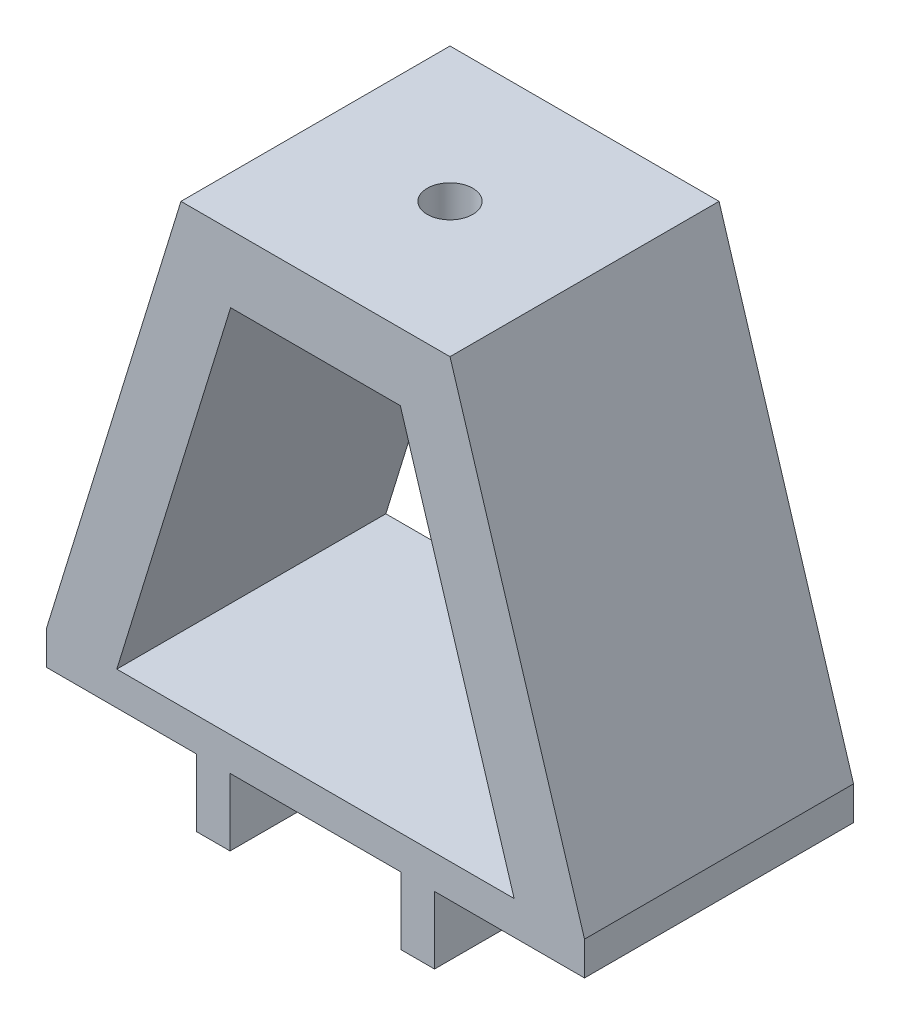
SolidWorks part; units mm, degrees
ref_plane "Front Plane" through (0, 0, 0) normal (0, 0, 1) x (1, 0, 0)
ref_plane "Top Plane" through (0, 0, 0) normal (0, 1, 0) x (1, 0, 0)
ref_plane "Right Plane" through (0, 0, 0) normal (1, 0, 0) x (0, 0, -1)
sketch "Sketch1" plane through (0, 0, 0) normal (0, 1, 0) x (1, 0, 0)
  line L1 (-40, -20) -> (40, -20)
  line L2 (-40, -20) -> (-40, 20)
  line L3 (-40, 20) -> (40, 20)
  line L4 (40, -20) -> (40, 20)
  line L5 (-40, -20) -> (40, 20) construction
  line L6 (-40, 20) -> (40, -20) construction
  point P0 (0, 0)
  dimension "D1" = 40
  dimension "D2" = 80
extrude "Boss-Extrude1" add sketch "Sketch1" along normal blind 5
sketch "Sketch2" plane through (0, 0, 0) normal (0, -1, 0) x (1, 0, 0)
  line L0 (0, -1000) -> (0, 49000) construction
  line L1 (-40, 20) -> (40, 20) construction
  line L2 (12.7, 20) -> (17.7, 20)
  line L3 (12.7, 20) -> (12.7, -20)
  line L4 (12.7, -20) -> (17.7, -20)
  line L5 (17.7, 20) -> (17.7, -20)
  line L6 (40, -20) -> (-40, -20) construction
  line L7 (-12.7, -20) -> (-17.7, -20)
  line L8 (-17.7, 20) -> (-17.7, -20)
  line L9 (-12.7, 20) -> (-17.7, 20)
  line L10 (-12.7, 20) -> (-12.7, -20)
  dimension "D1" = 25.4
  dimension "D2" = 5
extrude "Boss-Extrude2" add sketch "Sketch2" along normal blind 10
sketch "Sketch3" plane through (-17.7, 0, 0) normal (-1, 0, 0) x (0, 0, 1)
  line L0 (-10, -5) -> (10, -5) construction
  line L1 (-20, 0) -> (20, 0) construction
  circle A0 centre (-10, -5) radius 2.2
  circle A1 centre (10, -5) radius 2.2
  point P4 (0, -5)
  dimension "D1" = 4.4
  dimension "D2" = 20
  dimension "D3" = 5
extrude "Cut-Extrude1" cut sketch "Sketch3" against normal through all
sketch "Sketch4" plane through (-17.7, 0, 0) normal (-1, 0, 0) x (0, 0, 1)
  line L1 (-7.8927, -1.35) -> (-12.1073, -1.35)
  line L2 (-12.1073, -1.35) -> (-14.2147, -5)
  line L3 (-14.2147, -5) -> (-12.1073, -8.65)
  line L4 (-12.1073, -8.65) -> (-7.8927, -8.65)
  line L5 (-7.8927, -8.65) -> (-5.7853, -5)
  line L6 (-5.7853, -5) -> (-7.8927, -1.35)
  line L7 (12.1073, -1.35) -> (7.8927, -1.35)
  line L8 (7.8927, -1.35) -> (5.7853, -5)
  line L9 (5.7853, -5) -> (7.8927, -8.65)
  line L10 (7.8927, -8.65) -> (12.1073, -8.65)
  line L11 (12.1073, -8.65) -> (14.2147, -5)
  line L12 (14.2147, -5) -> (12.1073, -1.35)
  circle A0 centre (-10, -5) radius 3.65 construction
  circle A1 centre (10, -5) radius 3.65 construction
  dimension "D1" = 7.3
extrude "Cut-Extrude2" cut sketch "Sketch4" against normal blind 3
sketch "Sketch7" plane through (0, 0, -20) normal (0, 0, -1) x (-1, 0, 0)
  line L0 (0, -1000) -> (0, 49000) construction
  line L1 (-12.6143, 60) -> (12.6143, 60)
  line L2 (12.6143, 60) -> (29.5373, 5)
  line L3 (-40, 5) -> (40, 5) construction
  line L4 (29.5373, 5) -> (40, 5)
  line L5 (40, 5) -> (20, 70)
  line L6 (20, 70) -> (-20, 70)
  line L7 (-12.7, 0) -> (12.7, 0) construction
  line L8 (-40, 5) -> (-20, 70)
  line L9 (-12.6143, 60) -> (-29.5373, 5)
  point P15 (0, 70)
  point P18 (0, 60)
  line M15 (40, 5) -> (-40, 5)
  dimension "D1" = 20
  dimension "D2" = 10
  dimension "D3" = 10
  dimension "D4" = 70
extrude "Boss-Extrude3" add sketch "Sketch7" against normal up to surface (40 mm away) contours L0 L1 L2 L5 L6 M15 | L1 L0 L6 L8 L9 M15 up to face at (0, -2.5, 20)
sketch "Sketch5" plane through (0, 60, 0) normal (0, -1, 0) x (-1, 0, 0)
  point P0 (0, 0)
hole_wizard "CBORE for 1/4 Square Head Bolt1" positions "Sketch5" profile "Sketch6" counterbore size "1/4" standard "ANSI Inch" end condition through all
sketch "Sketch6" plane through (0, 60, 0) normal (1, 0, 0) x (0, 0, -1)
  line L0 (0, 0) -> (0, 10)
  line L1 (0, 10) -> (3.3782, 10)
  line L3 (3.3782, 10) -> (3.3782, 4.7752)
  line L4 (8.3337, 4.7752) -> (3.3782, 4.7752)
  line L5 (8.3337, 4.7752) -> (8.3337, 0.635)
  line L6 (8.3337, 0.635) -> (8.9687, 0)
  line L7 (8.9687, 0) -> (0, 0)
  line L8 (-8.3337, 0.635) -> (-8.9687, 0) construction
  line L11 (0, -6.35) -> (0, 107.95) construction
  dimension "Thru Hole Dia." = 6.7564
  dimension "Thru Hole Depth" = 10
  dimension "C'Bore Dia." = 16.6675
  dimension "C'Bore Depth" = 4.7752
  dimension "Near C'Sink Dia." = 17.9375
  dimension "Near C'Sink Angle" = 90
